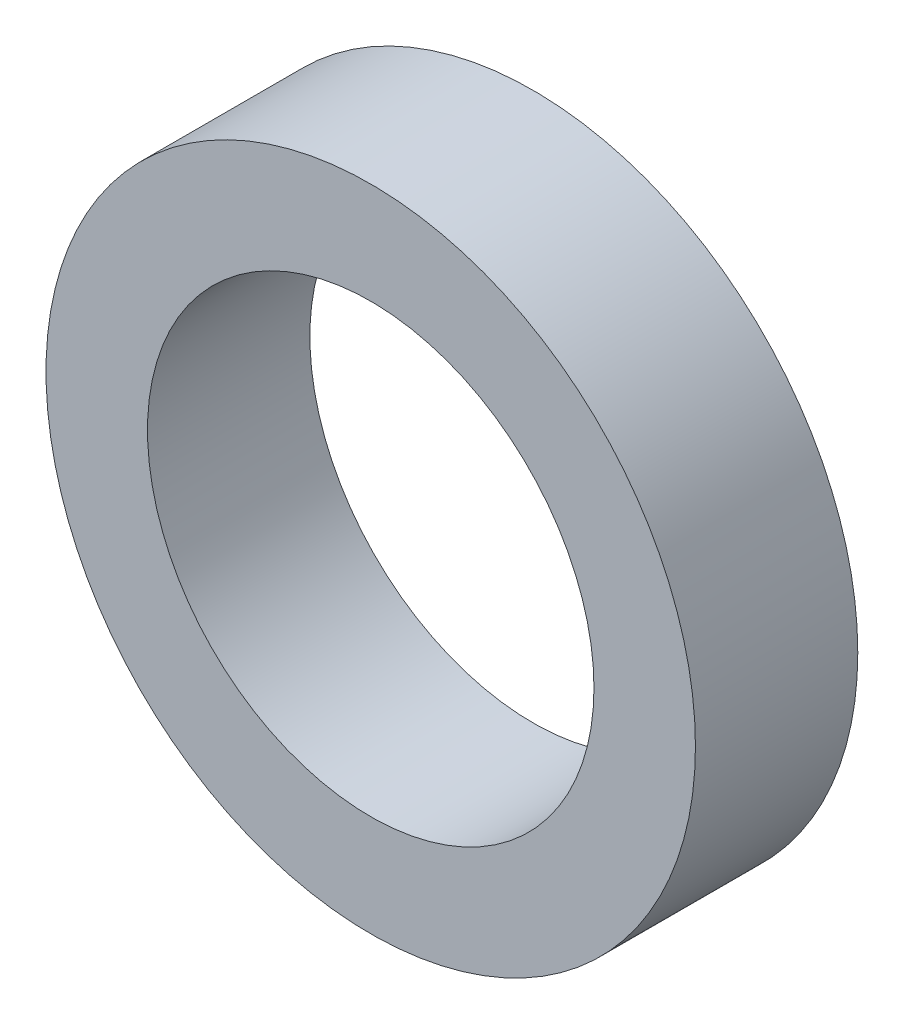
SolidWorks part; units mm, degrees
ref_plane "前视基准面" through (0, 0, 0) normal (0, 0, 1) x (1, 0, 0)
ref_plane "上视基准面" through (0, 0, 0) normal (0, 1, 0) x (1, 0, 0)
ref_plane "右视基准面" through (0, 0, 0) normal (1, 0, 0) x (0, 0, -1)
sketch "草图1" plane through (0, 0, 0) normal (0, 0, 1) x (1, 0, 0)
  circle A0 centre (0, 0) radius 5.5
  circle A1 centre (0, 0) radius 8
  dimension "D1" = 11
extrude "凸台-拉伸1" add sketch "草图1" along normal blind 4
